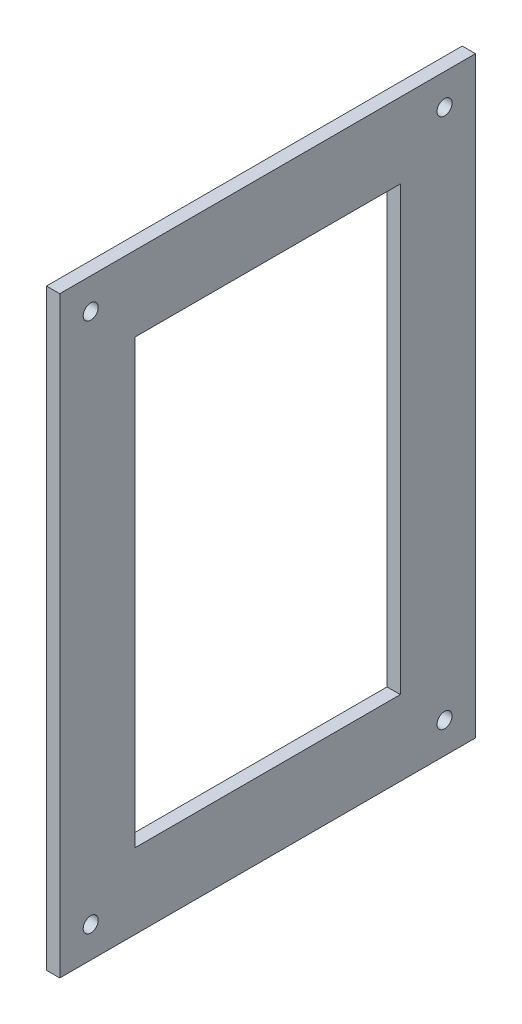
SolidWorks part; units mm, degrees
ref_plane "Front Plane" through (0, 0, 0) normal (0, 0, 1) x (1, 0, 0)
ref_plane "Top Plane" through (0, 0, 0) normal (0, 1, 0) x (1, 0, 0)
ref_plane "Right Plane" through (0, 0, 0) normal (1, 0, 0) x (0, 0, -1)
other "Configuration Table"
sketch "Sketch1" plane through (0, 0, 0) normal (1, 0, 0) x (0, 0, -1)
  line L1 (47, 73) -> (-47, 73)
  line L2 (47, 73) -> (47, 207)
  line L3 (47, 207) -> (-47, 207)
  line L4 (-47, 73) -> (-47, 207)
  line L5 (47, 73) -> (-47, 207) construction
  line L6 (47, 207) -> (-47, 73) construction
  point P0 (0, 140)
extrude "flange" add sketch "Sketch1" along normal blind 3 from offset 98 separate body
sketch "Sketch2" plane through (0, 0, 0) normal (1, 0, 0) x (0, 0, -1)
  line L1 (30, 90) -> (-30, 90)
  line L2 (30, 90) -> (30, 190)
  line L3 (30, 190) -> (-30, 190)
  line L4 (-30, 90) -> (-30, 190)
  line L5 (30, 90) -> (-30, 190) construction
  line L6 (30, 190) -> (-30, 90) construction
  circle A0 centre (40, 80) radius 1.7
  circle A1 centre (-40, 80) radius 1.7
  circle A2 centre (40, 200) radius 1.7
  circle A3 centre (-40, 200) radius 1.7
  point P0 (0, 140)
extrude "Port_and_M3_holes" cut sketch "Sketch2" against normal through all and the other way through all
